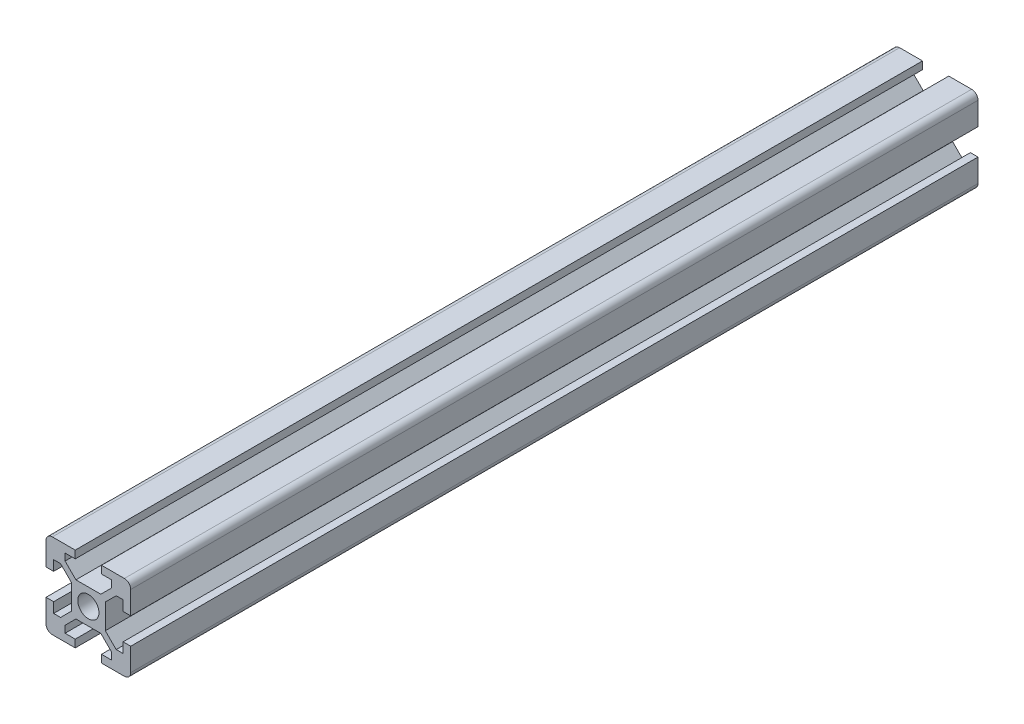
SolidWorks part; units mm, degrees
ref_plane "前视基准面" through (0, 0, 0) normal (0, 0, 1) x (1, 0, 0)
ref_plane "上视基准面" through (0, 0, 0) normal (0, 1, 0) x (1, 0, 0)
ref_plane "右视基准面" through (0, 0, 0) normal (1, 0, 0) x (0, 0, -1)
sketch "草图1" plane through (0, 0, 0) normal (0, 0, 1) x (1, 0, 0)
  line L0 (5.5, -8.2) -> (5.5, -6.5607)
  line L1 (-8.5, -10) -> (-3.1, -10)
  line L2 (-10, -8.5) -> (-10, -3.1)
  line L3 (-8.5, 10) -> (-3.1, 10)
  line L4 (10, -8.5) -> (10, -3.1)
  line L5 (-10, -10) -> (10, 10) construction
  line L6 (-10, 10) -> (10, -10) construction
  line L7 (8.2, 5.5) -> (6.5607, 5.5)
  line L8 (-2.9393, 4) -> (2.9393, 4)
  line L9 (4, 2.9393) -> (4, -2.9393)
  line L10 (2.9393, -4) -> (-2.9393, -4)
  line L11 (-4, -2.9393) -> (-4, 2.9393)
  line L12 (5.5, 6.5607) -> (5.5, 8.2)
  line L13 (6.5607, -5.5) -> (8.2, -5.5)
  line L14 (-8.2, -5.5) -> (-6.5607, -5.5)
  line L15 (-5.5, -6.5607) -> (-5.5, -8.2)
  line L16 (-5.5, 8.2) -> (-5.5, 6.5607)
  line L17 (-6.5607, 5.5) -> (-8.2, 5.5)
  line L18 (4, 2.9393) -> (6.5607, 5.5)
  line L19 (2.9393, 4) -> (5.5, 6.5607)
  line L20 (2.9393, -4) -> (5.5, -6.5607)
  line L21 (-4, 2.9393) -> (-6.5607, 5.5)
  line L22 (4, -2.9393) -> (6.5607, -5.5)
  line L23 (-2.9393, 4) -> (-5.5, 6.5607)
  line L24 (-4, -2.9393) -> (-6.5607, -5.5)
  line L25 (-2.9393, -4) -> (-5.5, -6.5607)
  line L26 (8.2, 3.1) -> (8.2, 5.5)
  line L27 (8.2, 3.1) -> (10, 3.1)
  line L28 (3.1, -8.2) -> (5.5, -8.2)
  line L29 (3.1, -8.2) -> (3.1, -10)
  line L30 (8.2, -3.1) -> (10, -3.1)
  line L31 (8.2, -3.1) -> (8.2, -5.5)
  line L32 (-3.1, -8.2) -> (-3.1, -10)
  line L33 (-3.1, -8.2) -> (-5.5, -8.2)
  line L34 (-8.2, -3.1) -> (-8.2, -5.5)
  line L35 (-8.2, -3.1) -> (-10, -3.1)
  line L36 (-8.2, 3.1) -> (-10, 3.1)
  line L37 (-8.2, 3.1) -> (-8.2, 5.5)
  line L38 (-3.1, 8.2) -> (-5.5, 8.2)
  line L39 (-3.1, 8.2) -> (-3.1, 10)
  line L40 (3.1, 8.2) -> (3.1, 10)
  line L41 (3.1, 8.2) -> (5.5, 8.2)
  line L42 (10, 3.1) -> (10, 8.5)
  line L43 (3.1, 10) -> (8.5, 10)
  line L44 (-10, 3.1) -> (-10, 8.5)
  line L45 (3.1, -10) -> (8.5, -10)
  arc A0 (8.5, -10) -> (10, -8.5) centre (8.5, -8.5) ccw
  arc A1 (-10, 8.5) -> (-8.5, 10) centre (-8.5, 8.5) cw
  arc A2 (-8.5, -10) -> (-10, -8.5) centre (-8.5, -8.5) cw
  arc A3 (8.5, 10) -> (10, 8.5) centre (8.5, 8.5) cw
  circle A4 centre (0, 0) radius 2.5
  point P0 (0, 0)
  point P39 (0, 0)
  point P56 (0, 0)
  point P73 (0, 0)
  dimension "D3" = 1.5
  dimension "D4" = 4
  dimension "D1" = 20
  dimension "D5" = 4
  dimension "D6" = 4
extrude "凸台-拉伸2" add sketch "草图1" against normal blind 200
scale "Scale1" bodies to scale 107 scale about origin uniform scaling yes scale factor 2.5
